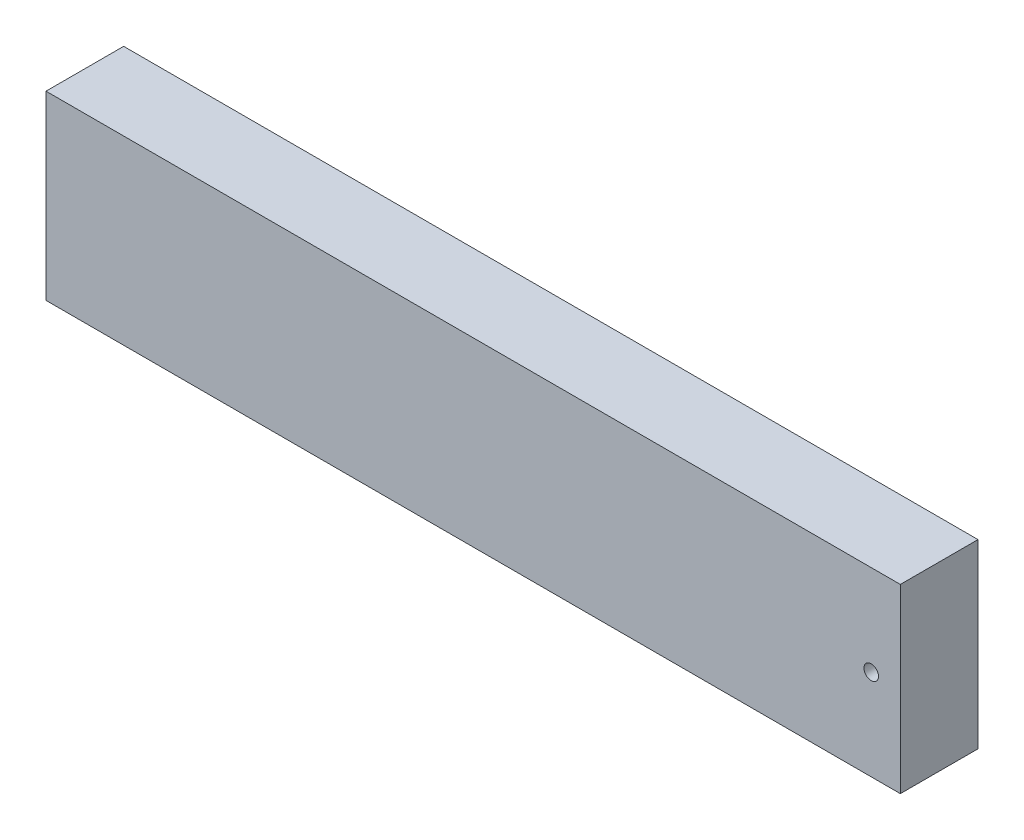
SolidWorks part; units mm, degrees
material "Pine"
ref_plane "Front Plane" through (0, 0, 0) normal (0, 0, 1) x (1, 0, 0)
ref_plane "Top Plane" through (0, 0, 0) normal (0, 1, 0) x (1, 0, 0)
ref_plane "Right Plane" through (0, 0, 0) normal (1, 0, 0) x (0, 0, -1)
sketch "Sketch1" plane through (0, 0, 0) normal (0, 0, 1) x (1, 0, 0)
  line L0 (0, 0) -> (0, 88.9)
  line L1 (0, 88.9) -> (419.1, 88.9)
  line L3 (419.1, 0) -> (0, 0)
  line L4 (419.1, 88.9) -> (419.1, 0)
  dimension "D2" = 88.9
  dimension "D3" = 419.1
extrude "Boss-Extrude1" add sketch "Sketch1" along normal blind 38.1
hole_wizard "9/32 (0.28125) Diameter Hole1" positions "Sketch2" profile "Sketch3" hole size "9/32" standard "ANSI Inch" end condition through all
sketch "Sketch2" plane through (0, 0, 38.1) normal (0, 0, 1) x (1, 0, 0)
  line L0 (0, 88.9) -> (0, 0) construction
  line L2 (0, 0) -> (419.1, 0) construction
  point P2 (404.8125, 44.45)
  dimension "D1" = 404.8125
  dimension "D2" = 44.45
sketch "Sketch3" plane through (404.8125, 44.45, 38.1) normal (1, 0, 0) x (0, -1, 0)
  line L0 (0, 0) -> (0, 38.1)
  line L1 (0, 38.1) -> (3.5719, 38.1)
  line L2 (3.5719, 38.1) -> (3.5719, 0)
  line L5 (3.5719, 0) -> (0, 0)
  line L11 (0, -6.35) -> (0, 107.95) construction
  dimension "Thru Hole Dia." = 7.1437
  dimension "Thru Hole Depth" = 38.1
